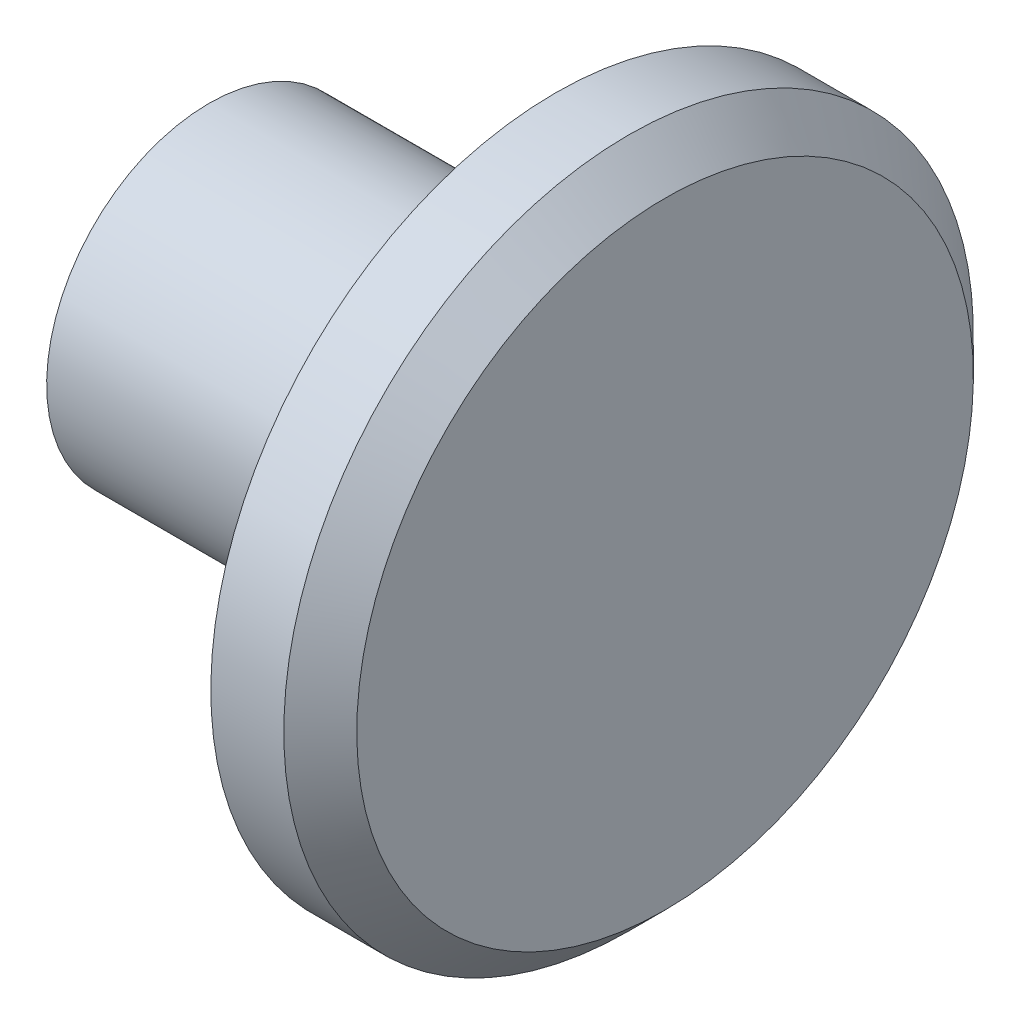
SolidWorks part; units mm, degrees
ref_plane "Front Plane" through (0, 0, 0) normal (0, 0, 1) x (1, 0, 0)
ref_plane "Top Plane" through (0, 0, 0) normal (0, 1, 0) x (1, 0, 0)
ref_plane "Right Plane" through (0, 0, 0) normal (1, 0, 0) x (0, 0, -1)
sketch "Sketch1" plane through (0, 0, 0) normal (0, 0, 1) x (1, 0, 0)
  line L3 (-6.25, -4.45) -> (3.25, -4.45)
  line L8 (-6.25, -4.45) -> (-6.25, 0)
  line L13 (3.25, -4.45) -> (3.25, -9.45)
  line L14 (3.25, -9.45) -> (6.25, -9.45)
  line L15 (6.25, -9.45) -> (6.25, 0)
  line L16 (6.25, 0) -> (-6.25, 0)
  point P0 (0, 0)
  dimension "D1" = 12.5
  dimension "D2" = 3
  dimension "D3" = 5
  dimension "D5" = 4.45
  dimension "D6" = 9.5
revolve "Revolve1" add sketch "Sketch1" angle 360 about L16
chamfer "Chamfer1" distance 1 angle 45 1 edges at (6.25, 9.45, 0)
